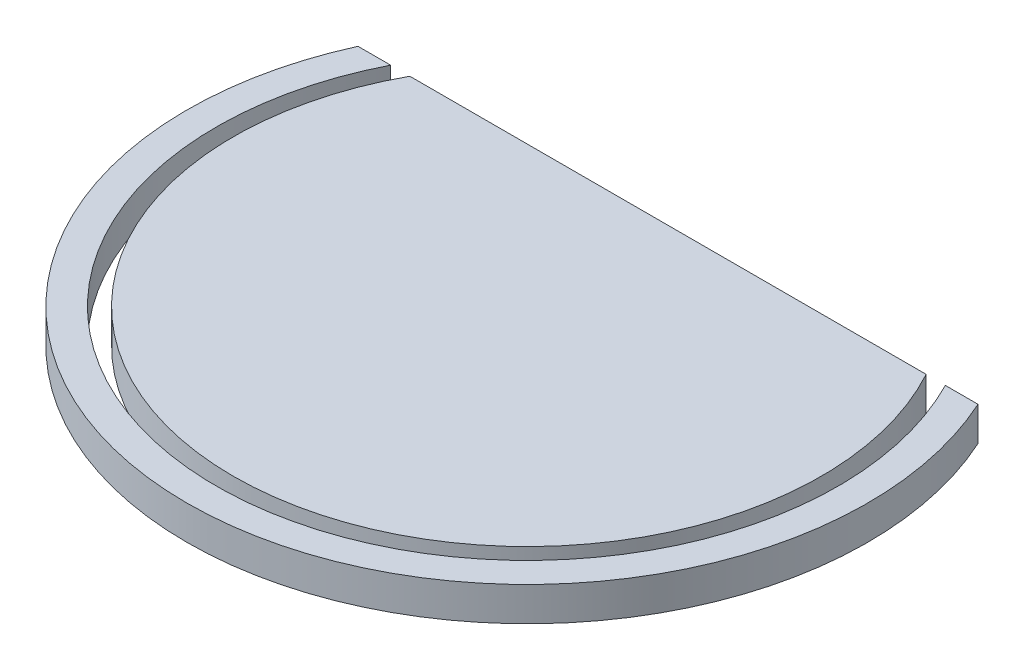
SolidWorks part; units mm, degrees
ref_plane "Ebene vorne" through (0, 0, 0) normal (0, 0, 1) x (1, 0, 0)
ref_plane "Ebene oben" through (0, 0, 0) normal (0, 1, 0) x (1, 0, 0)
ref_plane "Ebene rechts" through (0, 0, 0) normal (1, 0, 0) x (0, 0, -1)
sketch "Skizze1" plane through (0, 0, 0) normal (0, 1, 0) x (1, 0, 0)
  line L0 (91.0598, 41.3293) -> (-91.0598, 41.3293)
  arc A0 (-91.0598, 41.3293) -> (91.0598, 41.3293) centre (0, 0) ccw
  arc A1 (38.9066, 79.8897) -> (60.3864, 65.1888) centre (0, 0) ccw construction
  arc A6 (40.0012, 82.1374) -> (62.0853, 67.0228) centre (0, 0) ccw
  arc A7 (37.812, 77.6421) -> (58.6875, 63.3548) centre (0, 0) ccw
  arc A8 (37.812, 77.6421) -> (40.0012, 82.1374) centre (38.9066, 79.8897) ccw
  arc A9 (62.0853, 67.0228) -> (58.6875, 63.3548) centre (60.3864, 65.1888) ccw
  point P6 (-50.1877, -73.33)
  dimension "D1" = 200
  dimension "D2" = 5
extrude "Aufsatz-Linear austragen1" add sketch "Skizze1" along normal blind 10 contours L0 A7 | A6 L0 A0
